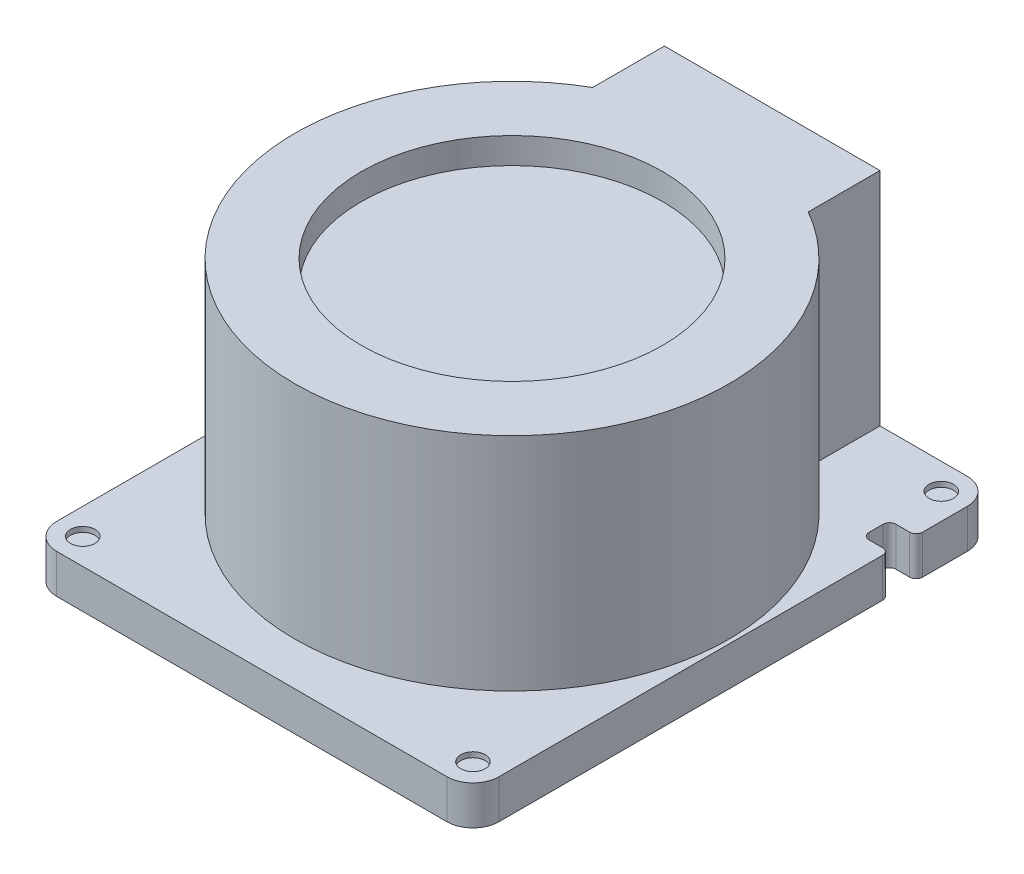
SolidWorks part; units mm, degrees
ref_plane "Front Plane" through (0, 0, 0) normal (0, 0, 1) x (1, 0, 0)
ref_plane "Top Plane" through (0, 0, 0) normal (0, 1, 0) x (1, 0, 0)
ref_plane "Right Plane" through (0, 0, 0) normal (1, 0, 0) x (0, 0, -1)
sketch "Sketch1" plane through (0, 0, 0) normal (0, 1, 0) x (1, 0, 0)
  line L0 (-16.5, 14.066) -> (-15.4532, 14.066)
  line L1 (-15, 20) -> (15, 20)
  line L3 (-15, -20) -> (15, -20)
  line L5 (-17, 20) -> (17, -20) construction
  line L6 (-17, -20) -> (17, 20) construction
  line L7 (-14.9532, 13.566) -> (-14.9532, 12.4901)
  line L8 (-15.4532, 11.9901) -> (-16.5, 11.9901)
  line L9 (0, 0) -> (0, -26.7249) construction
  line L10 (-17, 18) -> (-17, 14.566)
  line L11 (-17, 11.4901) -> (-17, -18)
  line L12 (17, 11.4901) -> (17, -18)
  line L13 (15.4532, 11.9901) -> (16.5, 11.9901)
  line L14 (14.9532, 13.566) -> (14.9532, 12.4901)
  line L15 (16.5, 14.066) -> (15.4532, 14.066)
  line L16 (17, 18) -> (17, 14.566)
  arc A0 (-15, 20) -> (-17, 18) centre (-15, 18) ccw
  arc A1 (-17, -18) -> (-15, -20) centre (-15, -18) ccw
  arc A2 (15, -20) -> (17, -18) centre (15, -18) ccw
  arc A3 (15, 20) -> (17, 18) centre (15, 18) cw
  arc A4 (17, 11.4901) -> (16.5, 11.9901) centre (16.5, 11.4901) ccw
  arc A5 (15.4532, 11.9901) -> (14.9532, 12.4901) centre (15.4532, 12.4901) cw
  arc A6 (16.5, 14.066) -> (17, 14.566) centre (16.5, 14.566) ccw
  arc A7 (14.9532, 13.566) -> (15.4532, 14.066) centre (15.4532, 13.566) cw
  arc A8 (-16.5, 11.9901) -> (-17, 11.4901) centre (-16.5, 11.4901) ccw
  arc A9 (-15.4532, 14.066) -> (-14.9532, 13.566) centre (-15.4532, 13.566) cw
  arc A10 (-14.9532, 12.4901) -> (-15.4532, 11.9901) centre (-15.4532, 12.4901) cw
  arc A11 (-16.5, 14.066) -> (-17, 14.566) centre (-16.5, 14.566) cw
  point P0 (0, 0)
  point P30 (17, 11.9901)
  point P33 (14.9532, 11.9901)
  point P36 (17, 14.066)
  point P39 (14.9532, 14.066)
  point P42 (-17, 11.9901)
  point P45 (-14.9532, 14.066)
  point P48 (-14.9532, 11.9901)
  point P51 (-17, 14.066)
  dimension "D1" = 2
  dimension "D2" = 2
  dimension "D3" = 0.5
extrude "Boss-Extrude1" add sketch "Sketch1" along normal blind 3
sketch "Sketch2" plane through (0, 3, 0) normal (0, 1, 0) x (1, 0, 0)
  line L0 (0, 0) -> (-27.9628, 0) construction
  line L1 (0, 0) -> (0, -22.4446) construction
  circle A0 centre (-15, 18) radius 0.939
  circle A1 centre (-15, -18) radius 0.939
  circle A2 centre (15, -18) radius 0.939
  circle A3 centre (15, 18) radius 0.939
extrude "Cut-Extrude1" cut sketch "Sketch2" against normal blind 0.4
sketch "Sketch4" plane through (0, 3, 0) normal (0, 1, 0) x (1, 0, 0)
  line L0 (8.2871, 14.4837) -> (8.2871, 20)
  line L1 (8.2871, 20) -> (-8.2871, 20)
  line L2 (0, 0) -> (0, 17.1916) construction
  line L3 (-8.2871, 14.4837) -> (-8.2871, 20)
  line L4 (15, 20) -> (-15, 20) construction
  arc A1 (-8.2871, 14.4837) -> (8.2871, 14.4837) centre (0, 0) ccw
  point P9 (0, 20)
  point P11 (-8.2871, 20)
extrude "Boss-Extrude2" add sketch "Sketch4" along normal blind 17
sketch "Sketch5" plane through (0, 20, 0) normal (0, 1, 0) x (1, 0, 0)
  circle A0 centre (0, 0) radius 11.5786
extrude "Cut-Extrude2" cut sketch "Sketch5" against normal blind 2
sketch "Sketch6" plane through (0, 18, 0) normal (0, 1, 0) x (1, 0, 0)
  line L0 (0, 11.5786) -> (0, -11.5786)
  line L1 (-11.5786, 0) -> (11.5786, 0)
  circle A0 centre (0, 0) radius 11.5786 construction
